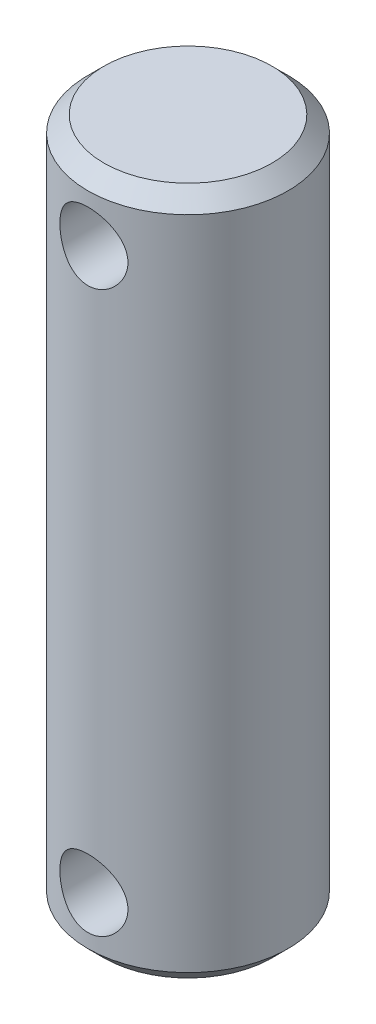
SolidWorks part; units mm, degrees
material "AISI 1045 Aço, trefilado"
ref_plane "Plano frontal" through (0, 0, 0) normal (0, 0, 1) x (1, 0, 0)
ref_plane "Plano superior" through (0, 0, 0) normal (0, 1, 0) x (1, 0, 0)
ref_plane "Plano direito" through (0, 0, 0) normal (1, 0, 0) x (0, 0, -1)
sketch "Esboço1" plane through (0, 0, 0) normal (0, 1, 0) x (1, 0, 0)
  circle A0 centre (0, 0) radius 12.5
  dimension "D1" = 25
extrude "Ressalto-extrusão1" add sketch "Esboço1" along normal mid plane 86
chamfer "Chanfro1" distance 2 angle 45 2 edges at (0, -43, 12.5) (0, 43, 12.5)
sketch "Esboço2" plane through (0, 0, 0) normal (0, 0, 1) x (1, 0, 0)
  line L0 (0, 43) -> (0, 35) construction
  line L1 (10.5, 43) -> (-10.5, 43) construction
  line L2 (0, -43) -> (0, -35) construction
  line L3 (-10.5, -43) -> (10.5, -43) construction
  circle A0 centre (0, 35) radius 4.25
  circle A1 centre (0, -35) radius 4.25
  dimension "D1" = 8.5
  dimension "D2" = 70
extrude "Corte-extrusão1" cut sketch "Esboço2" against normal mid plane 86
